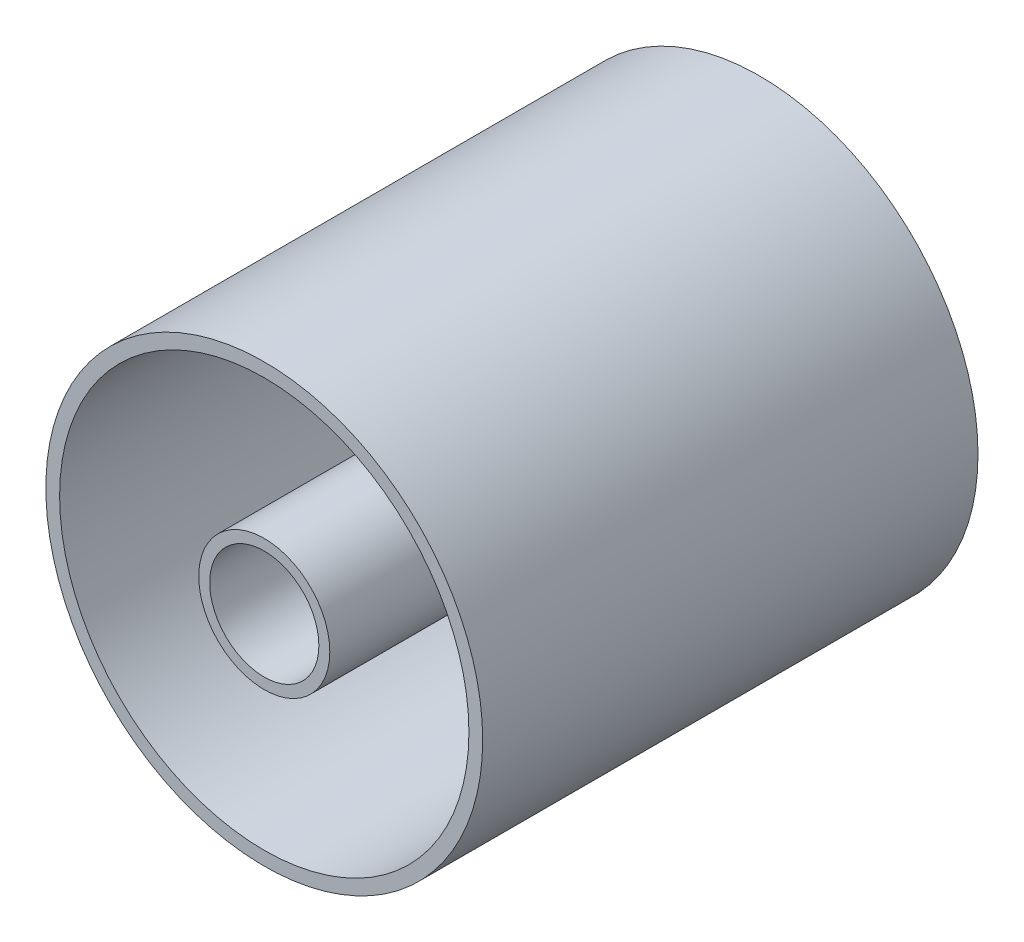
SolidWorks part; units mm, degrees
ref_plane "Alzado" through (0, 0, 0) normal (0, 0, 1) x (1, 0, 0)
ref_plane "Planta" through (0, 0, 0) normal (0, 1, 0) x (1, 0, 0)
ref_plane "Vista lateral" through (0, 0, 0) normal (1, 0, 0) x (0, 0, -1)
sketch "Croquis1" plane through (0, 0, 0) normal (0, 0, 1) x (1, 0, 0)
  circle A0 centre (0, 0) radius 31.75
  circle A1 centre (0, 0) radius 7.9375
  dimension "D1" = 63.5
  dimension "D2" = 15.875
extrude "Saliente-Extruir1" add sketch "Croquis1" along normal blind 2
sketch "Croquis2" plane through (0, 0, 2) normal (0, 0, 1) x (1, 0, 0)
  circle A0 centre (0, 0) radius 31.75
  circle A1 centre (0, 0) radius 29.75
  dimension "D1" = 2
extrude "Saliente-Extruir2" add sketch "Croquis2" along normal blind 70
sketch "Croquis3" plane through (0, 0, 2) normal (0, 0, 1) x (1, 0, 0)
  circle A0 centre (0, 0) radius 7.9375
  circle A1 centre (0, 0) radius 9.525
  point P3 (0, 0)
  dimension "D1" = 1.5875
extrude "Saliente-Extruir3" add sketch "Croquis3" along normal blind 70
